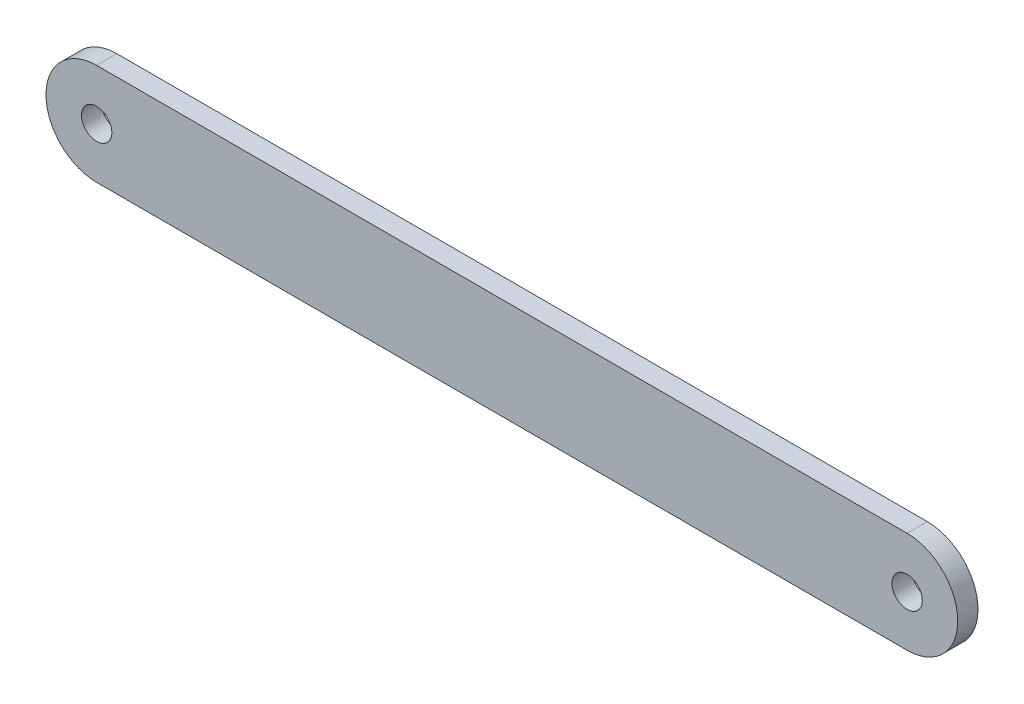
SolidWorks part; units mm, degrees
material "3.3535 (EN-AW 5754)"
ref_plane "Front" through (0, 0, 0) normal (0, 0, 1) x (1, 0, 0)
ref_plane "Top" through (0, 0, 0) normal (0, 1, 0) x (1, 0, 0)
ref_plane "Right" through (0, 0, 0) normal (1, 0, 0) x (0, 0, -1)
sketch "Esquisse1" plane through (0, 0, 0) normal (0, 0, 1) x (1, 0, 0)
  line L0 (-40, 0) -> (40, 0) construction
  line L1 (-40, 5) -> (40, 5)
  line L2 (-40, -5) -> (40, -5)
  arc A0 (-40, 5) -> (-40, -5) centre (-40, 0) ccw
  arc A1 (40, -5) -> (40, 5) centre (40, 0) ccw
  circle A2 centre (-40, 0) radius 1.5
  circle A3 centre (40, 0) radius 1.5
  point P2 (0, 0)
  dimension "D1" = 3
  dimension "D2" = 10
  dimension "D3" = 80
extrude "Boss.-Extru.1" add sketch "Esquisse1" along normal blind 2
